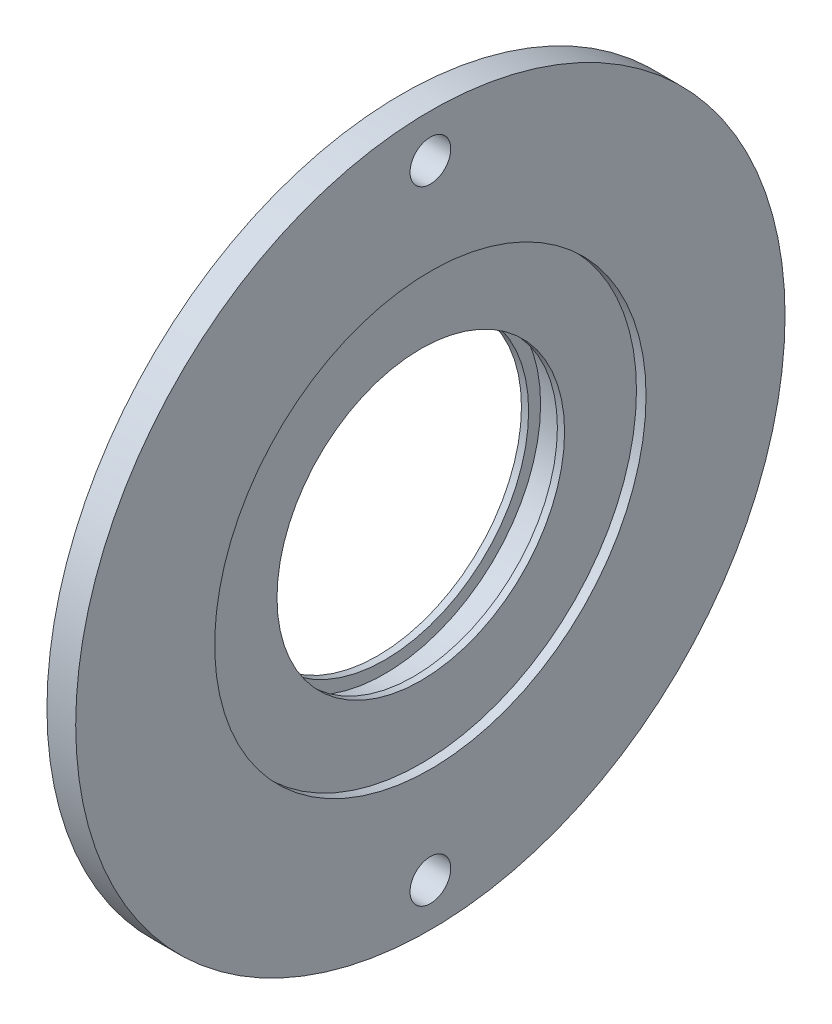
SolidWorks part; units mm, degrees
ref_plane "Plan de face" through (0, 0, 0) normal (0, 0, 1) x (1, 0, 0)
ref_plane "Plan de dessus" through (0, 0, 0) normal (0, 1, 0) x (1, 0, 0)
ref_plane "Plan de droite" through (0, 0, 0) normal (1, 0, 0) x (0, 0, -1)
sketch "Esquisse1" plane through (0, 0, 0) normal (0, 0, 1) x (1, 0, 0)
  line L0 (22, 0) -> (0, 0)
  line L1 (0, 0) -> (0, 100)
  line L2 (0, 100) -> (10, 100)
  line L3 (10, 100) -> (10, 148)
  line L4 (10, 148) -> (22, 148)
  line L5 (22, 148) -> (22, 0)
  dimension "D1" = 22
  dimension "D2" = 12
  dimension "D3" = 148
  dimension "D4" = 100
revolve "Révolution1" add sketch "Esquisse1" angle 360 about L0
sketch "Esquisse2" plane through (22, 0, 0) normal (1, 0, 0) x (0, 0, -1)
  line L0 (-130, 0) -> (130, 0)
  circle A0 centre (0, 0) radius 130
  circle A2 centre (0, 130) radius 8.5
  circle A3 centre (0, -130) radius 8.5
  dimension "D1" = 260
  dimension "D3" = 17
extrude "Enlèv. mat.-Extru.1" cut sketch "Esquisse2" against normal through all and the other way through all
sketch "Esquisse3" plane through (22, 0, 0) normal (1, 0, 0) x (0, 0, -1)
  circle A0 centre (0, 0) radius 90
  dimension "D1" = 180
extrude "Enlèv. mat.-Extru.2" cut sketch "Esquisse3" against normal blind 4
sketch "Esquisse6" plane through (18, 0, 0) normal (1, 0, 0) x (0, 0, -1)
  circle A0 centre (0, 0) radius 65
  dimension "D1" = 130
extrude "Enlèv. mat.-Extru.5" cut sketch "Esquisse6" against normal blind 12 from offset 3 offset against normal yes
sketch "Esquisse7" plane through (22, 0, 0) normal (1, 0, 0) x (0, 0, -1)
  circle A0 centre (0, 0) radius 60
  dimension "D1" = 120
extrude "Enlèv. mat.-Extru.6" cut sketch "Esquisse7" against normal through all both and the other way through all
